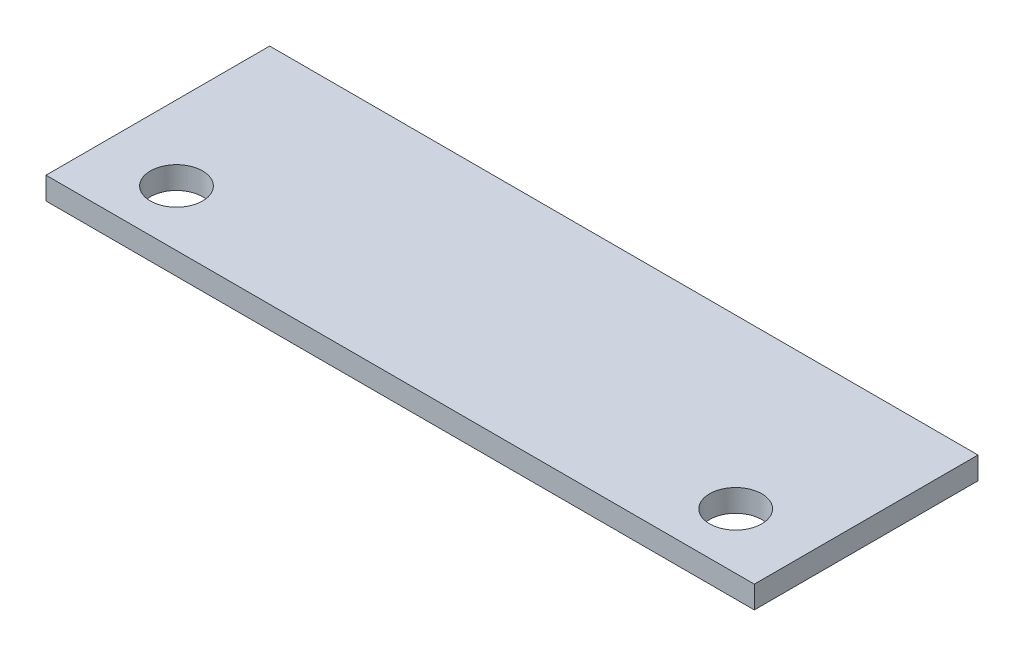
SolidWorks part; units mm, degrees
material "ASTM A36 Steel"
ref_plane "Front Plane" through (0, 0, 0) normal (0, 0, 1) x (1, 0, 0)
ref_plane "Top Plane" through (0, 0, 0) normal (0, 1, 0) x (1, 0, 0)
ref_plane "Right Plane" through (0, 0, 0) normal (1, 0, 0) x (0, 0, -1)
sketch "Sketch1" plane through (0, 0, 0) normal (0, 1, 0) x (1, 0, 0)
  line L1 (-95, -30) -> (95, -30)
  line L2 (-95, -30) -> (-95, 30)
  line L3 (-95, 30) -> (95, 30)
  line L4 (95, -30) -> (95, 30)
  line L5 (-95, -30) -> (95, 30) construction
  line L6 (-95, 30) -> (95, -30) construction
  point P0 (0, 0)
  dimension "D1" = 190
  dimension "D2" = 60
extrude "Boss-Extrude1" add sketch "Sketch1" along normal blind 6
sketch "Sketch2" plane through (0, 6, 0) normal (0, 1, 0) x (1, 0, 0)
  line L0 (-95, -30) -> (95, -30) construction
  line L1 (95, -30) -> (95, 30) construction
  line L2 (-95, 30) -> (-95, -30) construction
  circle A0 centre (75, -15) radius 7
  circle A1 centre (-75, -15) radius 7
  dimension "D1" = 14
  dimension "D2" = 15
  dimension "D3" = 20
  dimension "D4" = 14
  dimension "D5" = 20
  dimension "D6" = 15
extrude "Cut-Extrude1" cut sketch "Sketch2" against normal through all both and the other way through all
